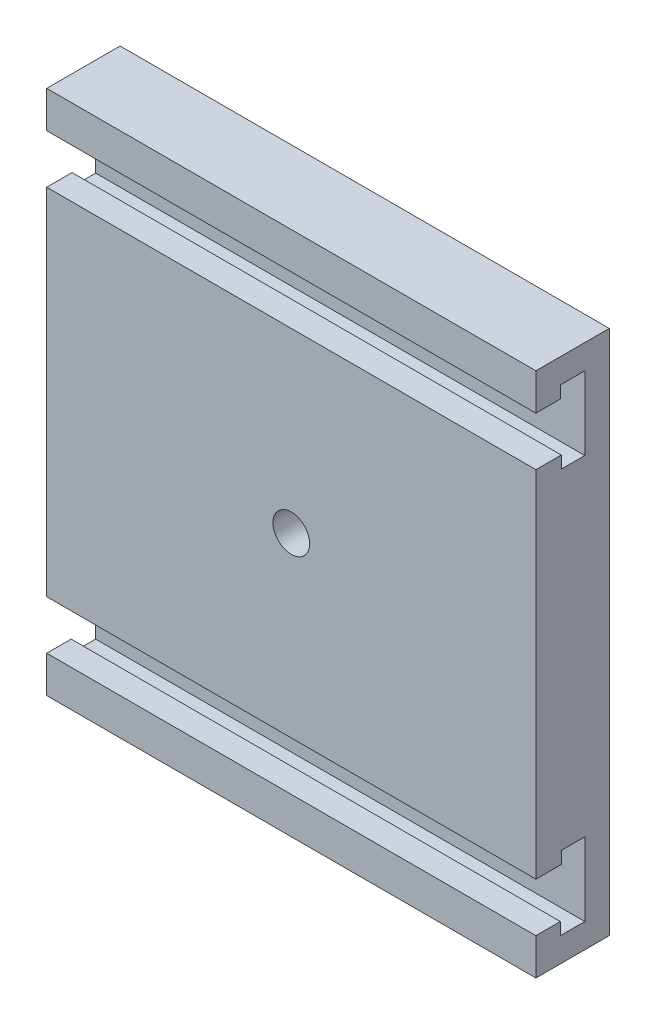
SolidWorks part; units mm, degrees
ref_plane "前视基准面" through (0, 0, 0) normal (0, 0, 1) x (1, 0, 0)
ref_plane "上视基准面" through (0, 0, 0) normal (0, 1, 0) x (1, 0, 0)
ref_plane "右视基准面" through (0, 0, 0) normal (1, 0, 0) x (0, 0, -1)
sketch "草图1" plane through (0, 0, 0) normal (0, 0, 1) x (1, 0, 0)
  line L1 (-20, -21.5) -> (20, -21.5)
  line L2 (-20, -21.5) -> (-20, 21.5)
  line L3 (-20, 21.5) -> (20, 21.5)
  line L4 (20, -21.5) -> (20, 21.5)
  line L5 (-20, -21.5) -> (20, 21.5) construction
  line L6 (-20, 21.5) -> (20, -21.5) construction
  circle A0 centre (0, 0) radius 1.5
  point P0 (0, 0)
  dimension "D2" = 3
  dimension "D1" = 43
  dimension "D3" = 40
extrude "凸台-拉伸1" add sketch "草图1" along normal blind 6
sketch "草图2" plane through (20, 0, 0) normal (1, 0, 0) x (0, 0, -1)
  line L0 (-6, 18.5) -> (-4, 18.5)
  line L1 (-6, -21.5) -> (-6, 21.5) construction
  line L2 (-4, 18.5) -> (-4, 19.5)
  line L3 (-4, 19.5) -> (-2, 19.5)
  line L4 (-2, 19.5) -> (-2, 13.5)
  line L5 (-2, 13.5) -> (-3.926, 13.5)
  line L6 (-3.926, 13.5) -> (-3.926, 14.5)
  line L7 (-3.926, 14.5) -> (-6, 14.5)
  line L8 (-6, 21.5) -> (0, 21.5) construction
  line L9 (-6, 18.5) -> (-6, 14.5)
  line L10 (0, 0) -> (-6, 0) construction
  line L11 (-6, -18.5) -> (-6, -14.5)
  line L12 (-3.926, -14.5) -> (-6, -14.5)
  line L13 (-3.926, -13.5) -> (-3.926, -14.5)
  line L14 (-2, -13.5) -> (-3.926, -13.5)
  line L15 (-2, -19.5) -> (-2, -13.5)
  line L16 (-4, -19.5) -> (-2, -19.5)
  line L17 (-4, -18.5) -> (-4, -19.5)
  line L18 (-6, -18.5) -> (-4, -18.5)
  dimension "D1" = 2
  dimension "D2" = 2
  dimension "D3" = 2
  dimension "D4" = 1
  dimension "D5" = 1
  dimension "D6" = 6
extrude "切除-拉伸1" cut sketch "草图2" against normal through all
